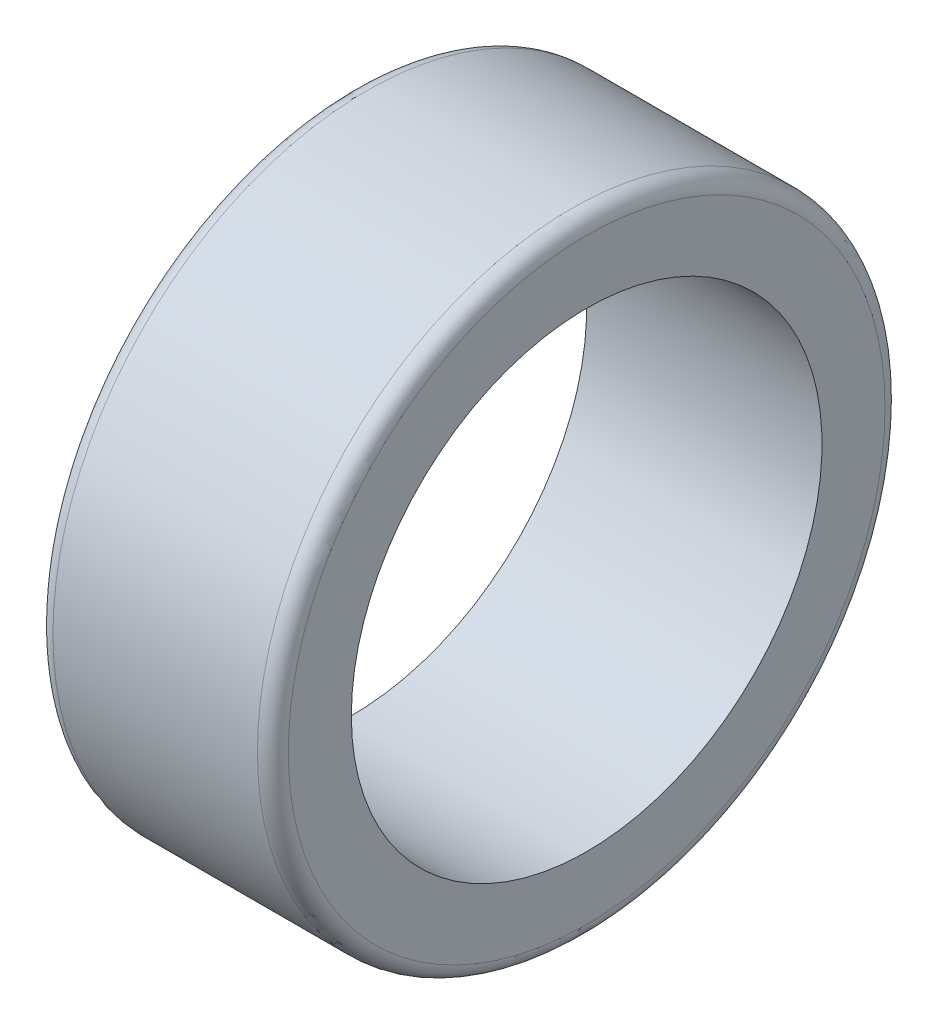
SolidWorks part; units mm, degrees
material "Custom Plastic"
ref_plane "Front Plane" through (0, 0, 0) normal (0, 0, 1) x (1, 0, 0)
ref_plane "Top Plane" through (0, 0, 0) normal (0, 1, 0) x (1, 0, 0)
ref_plane "Right Plane" through (0, 0, 0) normal (1, 0, 0) x (0, 0, -1)
sketch "Sketch1" plane through (0, 0, 0) normal (1, 0, 0) x (0, 0, -1)
  circle A0 centre (0, 0) radius 101.6
  circle A1 centre (0, 0) radius 76.2
  dimension "D1" = 203.2
  dimension "D2" = 25.4
extrude "Boss-Extrude1" add sketch "Sketch1" along normal mid plane 76.2
fillet "Fillet1" radius 5 2 edges at (-38.1, 0, -101.6) (38.1, 0, -101.6)
